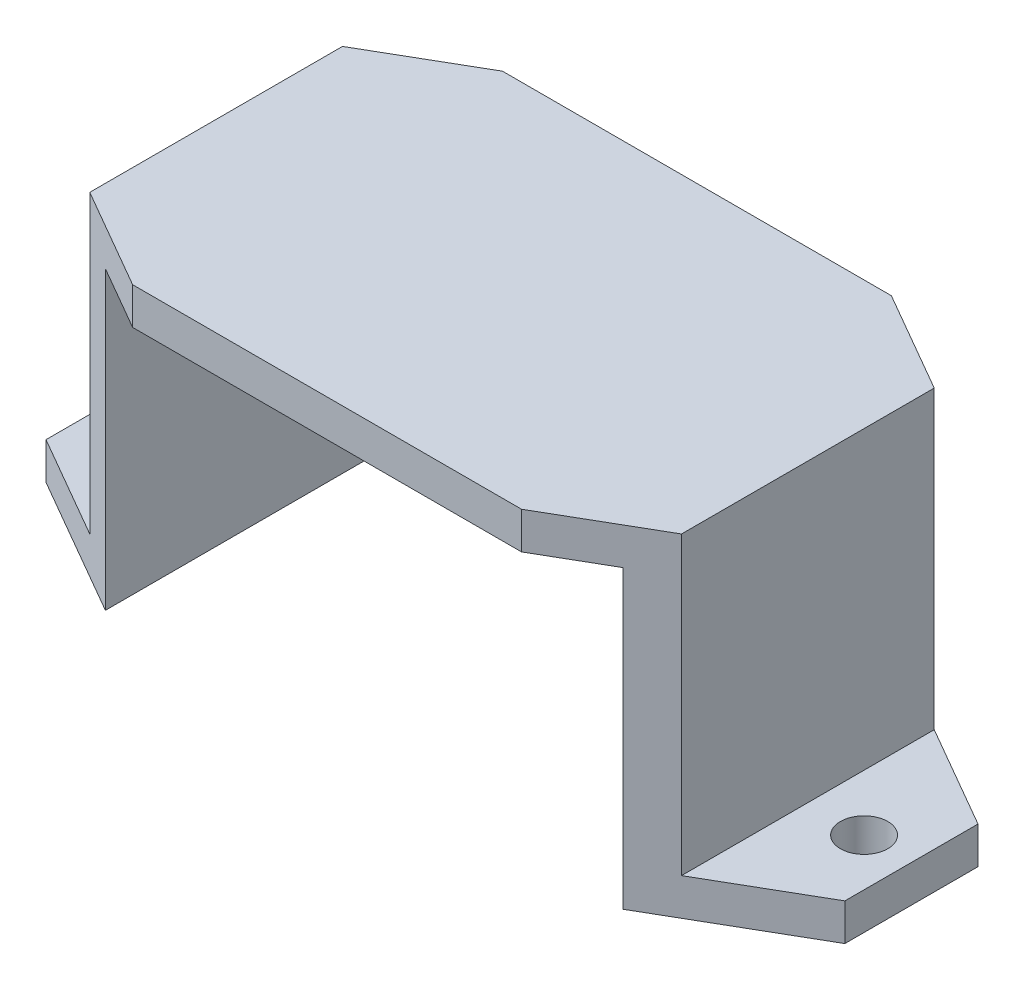
SolidWorks part; units mm, degrees
ref_plane "Front Plane" through (0, 0, 0) normal (0, 0, 1) x (1, 0, 0)
ref_plane "Top Plane" through (0, 0, 0) normal (0, 1, 0) x (1, 0, 0)
ref_plane "Right Plane" through (0, 0, 0) normal (1, 0, 0) x (0, 0, -1)
sketch "Sketch1" plane through (0, 0, 0) normal (0, 0, 1) x (1, 0, 0)
  line L0 (0, 0) -> (7, 0)
  line L5 (7, 0) -> (7, 20)
  line L6 (7, 20) -> (47, 20)
  line L7 (47, 20) -> (47, 0)
  line L8 (47, 0) -> (54, 0)
  dimension "D1" = 7
  dimension "D2" = 20
  dimension "D3" = 40
  dimension "D4" = 7
extrude "Extrude-Thin1" add sketch "Sketch1" along normal blind 25 thin
sketch "Sketch2" plane through (0, 20, 0) normal (0, 1, 0) x (1, 0, 0)
  line L0 (0, -8) -> (13.8564, 0)
  line L1 (0, -25) -> (0, 0) construction
  line L2 (7, 0) -> (47, 0) construction
  line L3 (0, -17) -> (13.8564, -25)
  line L4 (7, -25) -> (47, -25) construction
  line L5 (0, -25) -> (7, -25) construction
  line L6 (13.8564, 0) -> (13.8564, -25) construction
  line L7 (27, 0) -> (27, -25) construction
  line L8 (54, -17) -> (40.1436, -25)
  line L9 (54, -8) -> (40.1436, 0)
  line L10 (47, -25) -> (54, -25) construction
  line L11 (47, 0) -> (54, 0) construction
  line L12 (54, -25) -> (54, 0) construction
  line L13 (0, 0) -> (7, 0) construction
  line L14 (47, -25) -> (54, -25)
  line L15 (47, 0) -> (54, 0)
  line L16 (54, -25) -> (54, -17)
  line L17 (0, 0) -> (7, 0)
  line L18 (0, -25) -> (0, -17)
  line L19 (0, -25) -> (7, -25)
  line L20 (7, -25) -> (13.8564, -25)
  line L21 (7, 0) -> (13.8564, 0)
  line L22 (40.1436, 0) -> (47, 0)
  line L23 (40.1436, -25) -> (47, -25)
  line L24 (0, -8) -> (0, 0)
  line L25 (54, -8) -> (54, 0)
  dimension "D1" = 60
  dimension "D2" = 8
  dimension "D3" = 8
extrude "Cut-Extrude1" cut sketch "Sketch2" against normal through all
sketch "Sketch3" plane through (0, 0, 0) normal (0, 1, 0) x (1, 0, 0)
  line L0 (0, -12.5) -> (54, -12.5) construction
  line L1 (0, -17) -> (0, -8) construction
  line L2 (54, -17) -> (54, -8) construction
  circle A0 centre (50.8, -12.5) radius 1.6
  circle A1 centre (3.2, -12.5) radius 1.6
  dimension "D1" = 3.2
  dimension "D2" = 3.2
  dimension "D3" = 3.2
  dimension "D4" = 3.2
extrude "Cut-Extrude2" cut sketch "Sketch3" against normal through all
